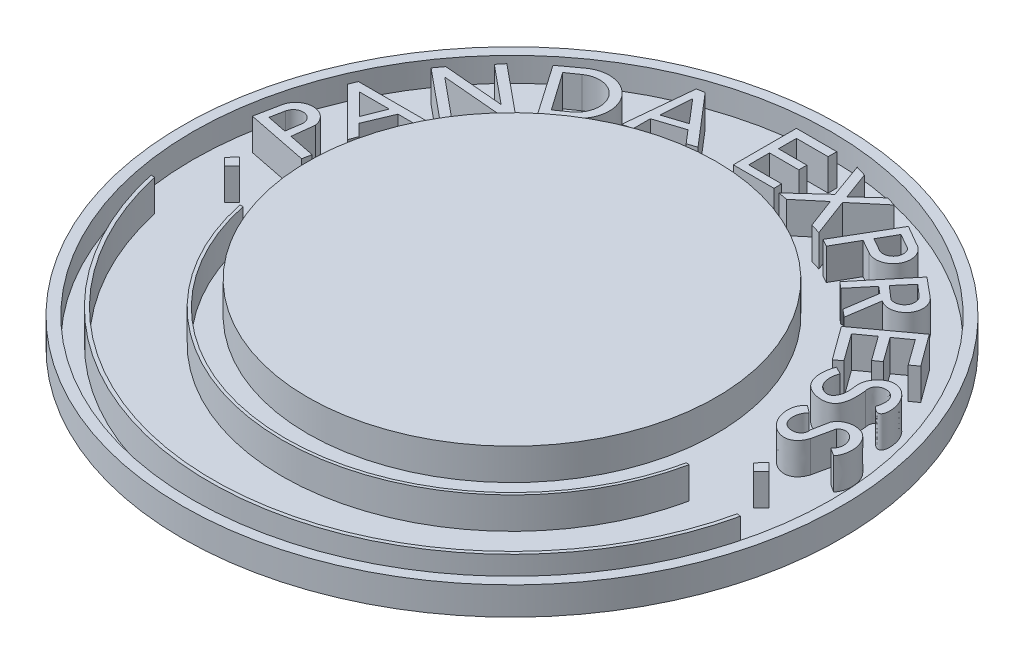
SolidWorks part; units mm, degrees
ref_plane "Front Plane" through (0, 0, 0) normal (0, 0, 1) x (1, 0, 0)
ref_plane "Top Plane" through (0, 0, 0) normal (0, 1, 0) x (1, 0, 0)
ref_plane "Right Plane" through (0, 0, 0) normal (1, 0, 0) x (0, 0, -1)
sketch "Sketch1" plane through (0, 0, 0) normal (0, 1, 0) x (1, 0, 0)
  line L0 (-346.7007, -44.5579) -> (319.966, -44.5579) construction
  line L1 (-334.1811, 33.6432) -> (-331.6592, 46.2527)
  line L2 (-331.6592, 46.2527) -> (-369.4238, 53.8057)
  line L3 (-369.4238, 53.8057) -> (-365.7729, 85.2106)
  line L7 (-414.9002, 86.376) -> (-421.9365, 51.1943)
  line L8 (-421.9365, 51.1943) -> (-334.1811, 33.6432)
  line L9 (-408.6661, 61.5433) -> (-380.3132, 55.8727)
  line L10 (-408.6661, 61.5433) -> (-404.7023, 81.3626)
  line L11 (-380.3132, 55.8727) -> (-376.9852, 77.7838)
  line L12 (-393.6662, 158.4552) -> (-324.9642, 89.7532)
  line L13 (-324.9642, 89.7532) -> (-320.483, 102.2012)
  line L14 (-320.483, 102.2012) -> (-336.9041, 118.6223)
  line L15 (-336.9041, 118.6223) -> (-320.483, 157.6341)
  line L16 (-320.483, 157.6341) -> (-297.8924, 157.6341)
  line L17 (-297.8924, 157.6341) -> (-292.8097, 169.7091)
  line L18 (-292.8097, 169.7091) -> (-388.9291, 169.7091)
  line L19 (-388.9291, 169.7091) -> (-393.6662, 158.4552)
  line L20 (-375.5127, 157.6341) -> (-345.0872, 127.2086)
  line L21 (-345.0872, 127.2086) -> (-332.976, 157.6341)
  line L22 (-332.976, 157.6341) -> (-375.5127, 157.6341)
  line L23 (-354.0443, 238.4507) -> (-285.0479, 181.6814)
  line L24 (-285.0479, 181.6814) -> (-277.2994, 191.0987)
  line L25 (-277.2994, 191.0987) -> (-332.976, 236.9086)
  line L26 (-332.976, 236.9086) -> (-245.7696, 229.4196)
  line L27 (-245.7696, 229.4196) -> (-236.178, 241.077)
  line L28 (-236.178, 241.077) -> (-305.1377, 297.816)
  line L29 (-305.1377, 297.816) -> (-313.2317, 287.9788)
  line L30 (-313.2317, 287.9788) -> (-258.7615, 243.1615)
  line L31 (-258.7615, 243.1615) -> (-345.0872, 250.5748)
  line L32 (-345.0872, 250.5748) -> (-354.0443, 238.4507)
  line L33 (-270.213, 328.7391) -> (-219.7816, 255.8859)
  line L34 (-254.3411, 326.7885) -> (-216.165, 272.3876)
  line L35 (-216.165, 272.3876) -> (-199.6234, 283.9957)
  line L36 (-254.3411, 326.7885) -> (-238.1873, 338.1245)
  line L37 (-270.213, 328.7391) -> (-243.7628, 348.1139)
  line L39 (-219.7816, 255.8859) -> (-194.2095, 274.9236)
  line L40 (-138.6799, 401.8724) -> (-148.2095, 304.4626)
  line L41 (-148.2095, 304.4626) -> (-134.6324, 307.9963)
  line L42 (-134.6324, 307.9963) -> (-134.6324, 332.1748)
  line L43 (-134.6324, 332.1748) -> (-94.0871, 345.3799)
  line L44 (-94.0871, 345.3799) -> (-78.0921, 326.7885)
  line L45 (-78.0921, 326.7885) -> (-65.2948, 330.9565)
  line L46 (-65.2948, 330.9565) -> (-127.9381, 403.7686)
  line L47 (-127.9381, 403.7686) -> (-138.6799, 401.8724)
  line L48 (-129.3219, 387.3889) -> (-100.6881, 353.9057)
  line L49 (-100.6881, 353.9057) -> (-132.2722, 343.6192)
  line L50 (-132.2722, 343.6192) -> (-129.3219, 387.3889)
  line L51 (-18.3874, 424.553) -> (-18.3874, 334.425)
  line L52 (-18.3874, 334.425) -> (39.7046, 334.425)
  line L53 (39.7046, 334.425) -> (39.7046, 345.3799)
  line L54 (39.7046, 345.3799) -> (-7.2816, 345.3799)
  line L55 (-7.2816, 345.3799) -> (-7.2816, 375.0039)
  line L56 (-7.2816, 375.0039) -> (34.5788, 375.0039)
  line L57 (34.5788, 375.0039) -> (34.5788, 386.5369)
  line L58 (34.5788, 386.5369) -> (-6.0002, 386.5369)
  line L59 (-6.0002, 386.5369) -> (-6.0002, 412.1657)
  line L60 (-6.0002, 412.1657) -> (39.2774, 412.1657)
  line L61 (39.2774, 412.1657) -> (39.2774, 424.553)
  line L62 (39.2774, 424.553) -> (-18.3874, 424.553)
  line L63 (73.0154, 419.9703) -> (87.8554, 415.4041)
  line L64 (87.8554, 415.4041) -> (102.3275, 376.0059)
  line L65 (102.3275, 376.0059) -> (132.7562, 403.7686)
  line L66 (132.7562, 403.7686) -> (146.144, 399.6493)
  line L67 (146.144, 399.6493) -> (106.1201, 365.9372)
  line L68 (106.1201, 365.9372) -> (126.5862, 311.6658)
  line L69 (126.5862, 311.6658) -> (112.2084, 316.0897)
  line L70 (112.2084, 316.0897) -> (96.2714, 358.3511)
  line L71 (96.2714, 358.3511) -> (62.3609, 329.7883)
  line L73 (48.795, 332.1748) -> (90.7867, 370.4874)
  line L74 (90.7867, 370.4874) -> (73.0154, 419.9703)
  line L75 (48.795, 332.1748) -> (62.3609, 329.7883)
  line L76 (137.9011, 306.2017) -> (182.8097, 383.3197)
  line L77 (182.8097, 383.3197) -> (209.9717, 367.5023)
  line L78 (148.6297, 300.2705) -> (167.7168, 333.7141)
  line L79 (173.4877, 343.4433) -> (191.4359, 333.1998)
  line L80 (173.4877, 343.4433) -> (187.4893, 367.9763)
  line L81 (187.4893, 367.9763) -> (209.9068, 355.1821)
  line L82 (137.9011, 306.2017) -> (148.6297, 300.2705)
  line L83 (167.7168, 333.7141) -> (187.6976, 322.3105)
  line L84 (258.6263, 333.904) -> (202.1762, 265.9376)
  line L85 (202.1762, 265.9376) -> (211.1619, 258.4745)
  line L86 (211.1619, 258.4745) -> (235.6347, 287.94)
  line L87 (235.6347, 287.94) -> (245.3288, 279.8884)
  line L88 (245.3288, 279.8884) -> (238.4202, 234.1113)
  line L89 (238.4202, 234.1113) -> (249.2216, 225.1401)
  line L90 (249.2216, 225.1401) -> (256.3521, 272.3876)
  line L91 (258.6263, 333.904) -> (286.0361, 311.1385)
  line L92 (242.2645, 296.4948) -> (261.1219, 318.3075)
  line L93 (261.1219, 318.3075) -> (276.3535, 305.1396)
  line L94 (242.2645, 296.4948) -> (260.8123, 280.4599)
  line L95 (258.6263, 211.7516) -> (331.1343, 264.8051)
  line L96 (331.1343, 264.8051) -> (364.4628, 219.2552)
  line L97 (364.4628, 219.2552) -> (354.0732, 211.7516)
  line L98 (354.0732, 211.7516) -> (327.8867, 248.0099)
  line L99 (327.8867, 248.0099) -> (307.0336, 232.9494)
  line L100 (307.0336, 232.9494) -> (332.1396, 198.1873)
  line L101 (332.1396, 198.1873) -> (322.3246, 191.0987)
  line L102 (322.3246, 191.0987) -> (297.2186, 225.8608)
  line L103 (297.2186, 225.8608) -> (274.9902, 209.8069)
  line L104 (274.9902, 209.8069) -> (302.9912, 171.0363)
  line L105 (302.9912, 171.0363) -> (293.3468, 164.0708)
  line L106 (293.3468, 164.0708) -> (258.6263, 211.7516)
  line L107 (305.5325, 157.9393) -> (316.4919, 152.1789)
  line L108 (332.1396, 89.7532) -> (342.9376, 81.4837)
  line L109 (401.4176, 53.8057) -> (413.1035, 46.2527)
  line L110 (369.1928, 85.2106) -> (364.4628, 61.5433)
  line L111 (375.2988, 51.1943) -> (381.9102, 81.4837)
  line L112 (375.2988, -8.5201) -> (386.3772, -19.5985)
  line L113 (386.3772, -19.5985) -> (375.2988, -30.6769)
  line L114 (375.2988, -30.6769) -> (364.4628, -19.841)
  line L115 (364.4628, -19.841) -> (375.2988, -8.5201)
  line L116 (-380.3132, -8.5201) -> (-369.4238, -19.4094)
  line L117 (-369.4238, -19.4094) -> (-380.3132, -30.2988)
  line L118 (-380.3132, -30.2988) -> (-390.9674, -19.6447)
  line L119 (-390.9674, -19.6447) -> (-380.3132, -8.5201)
  line L120 (316.7277, -67.3552) -> (320.8865, -68.2396)
  line L121 (-321.0733, -67.3552) -> (-316.7277, -67.3552)
  line L122 (416.2275, -94.0994) -> (421.2021, -95.2241)
  line L123 (-421.9365, -94.0994) -> (-416.2275, -94.0994)
  circle A0 centre (0, 0) radius 470.6251
  circle A1 centre (0, 0) radius 455.6203
  circle A2 centre (0, 0) radius 291.6875
  arc A3 (-404.7023, 81.3626) -> (-376.9852, 77.7838) centre (-390.9674, 78.6156) cw
  arc A4 (-414.9002, 86.376) -> (-365.7729, 85.2106) centre (-390.4388, 81.4837) cw
  arc A5 (-243.7628, 348.1139) -> (-194.2095, 274.9236) centre (-217.6296, 312.4372) cw
  arc A6 (-238.1873, 338.1245) -> (-199.6234, 283.9957) centre (-219.0983, 310.9227) cw
  arc A7 (191.4359, 333.1998) -> (209.9068, 355.1821) centre (198.669, 345.8734) ccw
  arc A8 (187.6976, 322.3105) -> (209.9717, 367.5023) centre (200.2075, 344.2297) ccw
  arc A9 (276.3535, 305.1396) -> (260.8123, 280.4599) centre (266.7068, 293.9811) cw
  arc A10 (286.0361, 311.1385) -> (256.3521, 272.3876) centre (270.4299, 292.3485) cw
  arc A11 (-316.7277, -67.3552) -> (316.7277, -67.3552) centre (0, 0) ccw
  arc A12 (-321.0733, -67.3552) -> (320.8865, -68.2396) centre (0, 0) ccw
  arc A13 (-421.4548, -94.0994) -> (421.2021, -95.2241) centre (0, 0) ccw
  arc A14 (-416.2275, -94.0994) -> (416.2275, -94.0994) centre (0, 0) ccw
  arc A15 (-352.1943, 240.9548) -> (-353.948, 238.3714) centre (0, 0) ccw
  spline S0 degree 3 poles (316.4919, 152.1789) (312.3414, 142.7699) (313.2525, 122.725) (336.7715, 115.4011) (347.1149, 135.1655) (336.9477, 157.7284) (363.7626, 188.1704) (403.0754, 163.8702) (398.5946, 119.5892) (381.9102, 137.2162) knots 0 0 0 0 0.168105 0.236644 0.306998 0.450025 0.594026 0.79272 1 1 1 1
  spline S1 degree 3 poles (355.4645, 149.3952) (356.6911, 137.6051) (359.0155, 100.6654) (298.5244, 110.1291) (300.6529, 145.0476) (305.5325, 157.9393) knots 0 0 0 0 0.323017 0.634299 1 1 1 1
  spline S2 degree 3 poles (355.4645, 149.3952) (352.0742, 163.1763) (370.4221, 169.9561) (385.9397, 155.4057) (383.9675, 143.3299) (381.9102, 137.2162) knots 0 0 0 0 0.494709 0.645784 1 1 1 1
  spline S3 degree 3 poles (342.9376, 81.4837) (334.2814, 75.3951) (331.7514, 41.8275) (366.9434, 47.0408) (364.4628, 61.5433) knots 0 0 0 0 0.511772 1 1 1 1
  spline S4 degree 3 poles (332.1396, 89.7532) (319.951, 80.1322) (323.3537, 34.869) (367.2901, 26.2786) (375.2988, 51.1943) knots 0 0 0 0 0.459951 1 1 1 1
  spline S5 degree 3 poles (401.4176, 53.8057) (407.8137, 58.6755) (410.1867, 78.2787) (390.5895, 90.3868) (381.9102, 81.4837) knots 0 0 0 0 0.43873 1 1 1 1
  spline S6 degree 3 poles (369.1928, 85.2106) (372.5077, 92.7399) (385.7349, 100.1354) (419.1515, 94.1779) (423.9969, 59.6722) (413.1035, 46.2527) knots 0 0 0 0 0.250574 0.443565 1 1 1 1
  spline S7 degree 3 poles (-78.0921, 180.367) (-37.0889, 192.9309) (-27.979, 201.5598) (36.7421, 189.9503) (41.1355, 188.5225) (53.6592, 176.9745) (58.9179, 200.4658) (75.2354, 202.388) (92.1036, 205.7858) (117.4602, 198.9456) (132.709, 176.253) (136.5726, 156.4078) (128.8024, 146.15) (135.1297, 141.9856) (142.2619, 135.998) (163.4026, 120.484) (178.3854, 104.0711) (187.6976, 89.7532) knots 0 0 0 0 0.408915 0.446676 0.508432 0.521003 0.564665 0.590555 0.63116 0.681705 0.759021 0.80184 0.817987 0.824477 0.847951 0.88494 1 1 1 1
  spline S8 degree 3 poles (187.6976, 89.7532) (201.0991, 73.6352) (214.3714, 50.8009) (229.9271, 14.9067) (233.3462, -14.611) (237.7795, -62.1326) (230.0214, -113.7709) (170.2864, -178.5152) (163.2306, -160.6397) (151.4349, -167.475) (151.342, -178.572) (127.4759, -198.7643) (153.1423, -183.3316) (121.7889, -210.1744) (109.4434, -220.5242) (80.1691, -238.4373) (45.4847, -248.6309) (6.8622, -248.8243) (-22.3974, -226.085) (-16.2768, -198.9703) (2.9072, -185.5434) (20.3945, -162.5088) (14.7668, -129.9117) (-9.0579, -120.2648) (-27.8423, -121.3259) (-43.8396, -132.483) (-45.5203, -149.2124) (-42.9755, -165.426) (-34.1556, -180.1922) (-29.3384, -198.4553) (-37.162, -221.9313) (-65.6583, -228.7044) (-89.9535, -220.6684) (-113.371, -206.9625) (-139.7167, -183.5767) (-165.1081, -153.9512) (-176.1619, -114.8641) (-181.5789, -78.6401) (-163.7548, -28.5407) (-155.3438, -8.9443) (-147.6978, -6.1591) (-153.0561, 8.047) (-156.7314, 20.8219) (-161.7207, 36.2701) (-162.1736, 58.5709) (-159.8698, 79.8853) (-154.7806, 97.6326) (-146.299, 109.7387) (-158.046, 118.4387) (-167.1919, 128.7328) (-175.6027, 147.6055) (-180.1477, 167.2483) (-175.9911, 186.3876) (-164.0023, 201.5832) (-149.7603, 211.8776) (-133.7311, 214.2281) (-119.9812, 215.6561) (-98.8032, 204.0351) (-85.9354, 190.9417) (-78.0921, 180.367) knots 0 0 0 0 0.000844 0.001065 0.001579 0.002026 0.003033 0.00344 0.005796 0.006184 0.006936 0.007485 0.011587 0.01843 0.025739 0.035795 0.049309 0.062457 0.073552 0.079975 0.086854 0.096501 0.107782 0.113287 0.120717 0.125951 0.131087 0.136402 0.142263 0.148033 0.15492 0.164336 0.173351 0.180327 0.191259 0.208518 0.218342 0.230862 0.247485 0.255897 0.314978 0.331296 0.360679 0.398702 0.435771 0.503678 0.532486 0.562212 0.575848 0.616947 0.653699 0.706745 0.744636 0.774819 0.830303 0.851583 0.878974 0.917277 1 1 1 1
  spline S9 degree 3 poles (-149.6371, 111.1185) (-142.6312, 115.6029) (-136.2585, 129.445) (-122.6049, 144.8267) (-104.8697, 163.1114) (-88.877, 173.301) (-78.0921, 180.367) knots 0 0 0 0 0.240964 0.440624 0.613108 1 1 1 1
  spline S10 degree 3 poles (48.795, 181.6814) (44.6124, 175.9442) (39.2378, 166.3266) (38.9908, 151.2109) (44.9831, 138.8316) (55.5945, 126.8512) (68.0852, 116.3399) (80.8951, 107.2319) (95.4859, 100.461) (110.4359, 112.1336) (114.6483, 103.1753) (117.8812, 96.2237) (119.3664, 84.0376) (124.0279, 71.1258) (125.5708, 49.3835) (120.6955, 23.3494) (104.9876, -9.9502) (84.5825, -32.9533) (65.8612, -46.9589) (48.1933, -58.1886) (47.7464, -59.3737) (34.9857, -66.7) (29.6004, -69.9443) (16.8797, -74.6949) (10.2696, -79.6149) (-14.6597, -88.1457) (-21.2371, -92.7249) (-51.6071, -92.3587) (-62.1691, -86.242) (-91.6733, -72.88) (-119.8582, -43.5566) (-119.7484, -40.6363) (-150.3874, 0) knots 0 0 0 0 0.030072 0.044194 0.06163 0.086156 0.110975 0.129708 0.152494 0.175208 0.180464 0.19015 0.208299 0.230698 0.247519 0.298921 0.339633 0.400413 0.426743 0.434868 0.476463 0.485034 0.51201 0.517015 0.530077 0.539586 0.602601 0.619824 0.694595 0.727365 0.914758 1 1 1 1
  spline S11 degree 3 poles (130.6037, 145.4015) (122.9198, 142.2798) (126.8408, 131.6969) (119.0885, 122.9486) (119.1957, 114.1478) (127.7845, 103.4708) (140.6899, 92.0872) (149.9132, 75.152) (160.5704, 59.8653) (165.2604, 40.44) (171.7519, 17.2986) (177.0446, -4.2592) (176.3586, -24.0389) (178.8532, -36.3982) (176.2746, -49.3457) (183.5383, -50.5193) (193.5995, -51.5363) (190.1513, -50.851) (206.302, -48.6749) (209.6555, -48.2309) (220.005, -38.3618) (228.1987, -29.2786) (232.6254, -21.4537) (233.3625, -16.0417) knots 0 0 0 0 0.06437 0.098503 0.12031 0.155601 0.244287 0.311271 0.366755 0.449117 0.52876 0.633684 0.693896 0.741636 0.783828 0.803672 0.809325 0.836913 0.845044 0.887189 0.924208 0.951984 1 1 1 1
  point P220 (0, 0)
  point P228 (0, 0)
  point P232 (196.4188, -50.0164)
  point P236 (187.6976, -50.9164)
  point P240 (0, 0)
  point P252 (0, 0)
extrude "Boss-Extrude1" add sketch "Sketch1" along normal blind 40 contours A0
sketch "Sketch9" plane through (0, 40, 0) normal (0, 1, 0) x (1, 0, 0)
  spline S0 degree 3 poles (2978.0314, -796.2808) (-16.9152, 250.608) (147.9652, 155.5352) (119.0885, 122.9486) (119.1957, 114.1478) (127.7845, 103.4708) (140.6899, 92.0872) (149.9132, 75.152) (160.5704, 59.8653) (165.2604, 40.44) (171.7519, 17.2986) (177.0446, -4.2592) (176.3586, -24.0389) (178.8532, -36.3982) (176.2746, -49.3457) (183.5383, -50.5193) (193.5995, -51.5363) (190.1513, -50.851) (206.302, -48.6749) (209.6555, -48.2309) (220.005, -38.3618) (266.9967, 13.7317) (241.466, 174.4019) (-2760.0738, 7.6653) knots -0.327832 -0.327832 -0.327832 -0.327832 0.06437 0.098503 0.12031 0.155601 0.244287 0.311271 0.366755 0.449117 0.52876 0.633684 0.693896 0.741636 0.783828 0.803672 0.809325 0.836913 0.845044 0.887189 0.924208 0.951984 1.534175 1.534175 1.534175 1.534175 only from (130.6037, 145.4015) to (233.3625, -16.0417) construction
  spline S1 degree 3 poles (-2525.2148, 1939.1592) (-139.6779, -35.9603) (-174.7638, 86.0664) (-122.6049, 144.8267) (-6.391, 264.6416) (318.0431, 140.3304) (-1988.9788, 2473.5674) knots -1.729055 -1.729055 -1.729055 -1.729055 0.240964 0.440624 0.613108 5.214717 5.214717 5.214717 5.214717 only from (-149.6371, 111.1185) to (-78.0921, 180.367) construction
  spline S2 degree 3 poles (-2895.7171, -391.2279) (485.014, 251.5012) (40.6959, 255.5227) (38.9908, 151.2109) (44.9831, 138.8316) (55.5945, 126.8512) (68.0852, 116.3399) (80.8951, 107.2319) (95.4859, 100.461) (110.4359, 112.1336) (114.6483, 103.1753) (117.8812, 96.2237) (119.3664, 84.0376) (124.0279, 71.1258) (125.5708, 49.3835) (120.6955, 23.3494) (104.9876, -9.9502) (84.5825, -32.9533) (65.8612, -46.9589) (48.1933, -58.1886) (47.7464, -59.3737) (34.9857, -66.7) (29.6004, -69.9443) (16.8797, -74.6949) (10.2696, -79.6149) (-14.6597, -88.1457) (-21.2371, -92.7249) (-51.6071, -92.3587) (-62.1691, -86.242) (-91.6733, -72.88) (-142.6253, -19.8698) (-98.8584, -54.3936) (-1990.5908, 2369.0085) knots -0.363673 -0.363673 -0.363673 -0.363673 0.030072 0.044194 0.06163 0.086156 0.110975 0.129708 0.152494 0.175208 0.180464 0.19015 0.208299 0.230698 0.247519 0.298921 0.339633 0.400413 0.426743 0.434868 0.476463 0.485034 0.51201 0.517015 0.530077 0.539586 0.602601 0.619824 0.694595 0.727365 0.914758 1.2467 1.2467 1.2467 1.2467 only from (48.795, 181.6814) to (-150.3874, 0) construction
  spline S3 degree 3 poles (130.6037, 145.4015) (122.9198, 142.2798) (126.8408, 131.6969) (119.0885, 122.9486) (119.1957, 114.1478) (127.7845, 103.4708) (140.6899, 92.0872) (149.9132, 75.152) (160.5704, 59.8653) (165.2604, 40.44) (171.7519, 17.2986) (177.0446, -4.2592) (176.3586, -24.0389) (178.8532, -36.3982) (176.2746, -49.3457) (183.5383, -50.5193) (193.5995, -51.5363) (190.1513, -50.851) (206.302, -48.6749) (209.6555, -48.2309) (220.005, -38.3618) (228.1987, -29.2786) (232.6254, -21.4537) (233.3625, -16.0417) knots 0 0 0 0 0.06437 0.098503 0.12031 0.155601 0.244287 0.311271 0.366755 0.449117 0.52876 0.633684 0.693896 0.741636 0.783828 0.803672 0.809325 0.836913 0.845044 0.887189 0.924208 0.951984 1 1 1 1
  spline S4 degree 3 poles (-149.6371, 111.1185) (-142.6312, 115.6029) (-136.2585, 129.445) (-122.6049, 144.8267) (-104.8697, 163.1114) (-88.877, 173.301) (-78.0921, 180.367) knots 0 0 0 0 0.240964 0.440624 0.613108 1 1 1 1
  spline S5 degree 3 poles (48.795, 181.6814) (44.6124, 175.9442) (39.2378, 166.3266) (38.9908, 151.2109) (44.9831, 138.8316) (55.5945, 126.8512) (68.0852, 116.3399) (80.8951, 107.2319) (95.4859, 100.461) (110.4359, 112.1336) (114.6483, 103.1753) (117.8812, 96.2237) (119.3664, 84.0376) (124.0279, 71.1258) (125.5708, 49.3835) (120.6955, 23.3494) (104.9876, -9.9502) (84.5825, -32.9533) (65.8612, -46.9589) (48.1933, -58.1886) (47.7464, -59.3737) (34.9857, -66.7) (29.6004, -69.9443) (16.8797, -74.6949) (10.2696, -79.6149) (-14.6597, -88.1457) (-21.2371, -92.7249) (-51.6071, -92.3587) (-62.1691, -86.242) (-91.6733, -72.88) (-119.8582, -43.5566) (-119.7484, -40.6363) (-150.3874, 0) knots 0 0 0 0 0.030072 0.044194 0.06163 0.086156 0.110975 0.129708 0.152494 0.175208 0.180464 0.19015 0.208299 0.230698 0.247519 0.298921 0.339633 0.400413 0.426743 0.434868 0.476463 0.485034 0.51201 0.517015 0.530077 0.539586 0.602601 0.619824 0.694595 0.727365 0.914758 1 1 1 1
sketch "Sketch8" plane through (0, 40, 0) normal (0, 1, 0) x (1, 0, 0)
  spline S0 degree 3 poles (-3074.5134, 227.2219) (254.7504, 12.5874) (-179.8145, 228.7955) (36.7421, 189.9503) (41.1355, 188.5225) (53.6592, 176.9745) (58.9179, 200.4658) (75.2354, 202.388) (92.1036, 205.7858) (117.4602, 198.9456) (132.709, 176.253) (136.5726, 156.4078) (128.8024, 146.15) (135.1297, 141.9856) (142.2619, 135.998) (373.3669, -33.5972) (84.1347, -663.1391) (-1196.3584, -2546.2808) knots -1.192778 -1.192778 -1.192778 -1.192778 0.408915 0.446676 0.508432 0.521003 0.564665 0.590555 0.63116 0.681705 0.759021 0.80184 0.817987 0.824477 0.847951 0.88494 2.743243 2.743243 2.743243 2.743243 only from (-78.0921, 180.367) to (187.6976, 89.7532) construction
  spline S1 degree 3 poles (-2426.7162, -1272.6169) (-203.71, 355.1144) (128.2316, 249.5652) (229.9271, 14.9067) (233.3462, -14.611) (237.7795, -62.1326) (230.0214, -113.7709) (170.2864, -178.5152) (163.2306, -160.6397) (151.4349, -167.475) (151.342, -178.572) (127.4759, -198.7643) (153.1423, -183.3316) (121.7889, -210.1744) (109.4434, -220.5242) (80.1691, -238.4373) (45.4847, -248.6309) (6.8622, -248.8243) (-22.3974, -226.085) (-16.2768, -198.9703) (2.9072, -185.5434) (20.3945, -162.5088) (14.7668, -129.9117) (-9.0579, -120.2648) (-27.8423, -121.3259) (-43.8396, -132.483) (-45.5203, -149.2124) (-42.9755, -165.426) (-34.1556, -180.1922) (-29.3384, -198.4553) (-37.162, -221.9313) (-65.6583, -228.7044) (-89.9535, -220.6684) (-113.371, -206.9625) (-139.7167, -183.5767) (-165.1081, -153.9512) (-176.1619, -114.8641) (-181.5789, -78.6401) (-163.7548, -28.5407) (-155.3438, -8.9443) (-147.6978, -6.1591) (-153.0561, 8.047) (-156.7314, 20.8219) (-161.7207, 36.2701) (-162.1736, 58.5709) (-159.8698, 79.8853) (-154.7806, 97.6326) (-146.299, 109.7387) (-158.046, 118.4387) (-167.1919, 128.7328) (-175.6027, 147.6055) (-180.1477, 167.2483) (-175.9911, 186.3876) (-164.0023, 201.5832) (-149.7603, 211.8776) (-133.7311, 214.2281) (-119.9812, 215.6561) (64.2797, 114.5464) (-235.442, -378.8952) (2614.1564, -1018.3453) knots -0.008742 -0.008742 -0.008742 -0.008742 0.000844 0.001065 0.001579 0.002026 0.003033 0.00344 0.005796 0.006184 0.006936 0.007485 0.011587 0.01843 0.025739 0.035795 0.049309 0.062457 0.073552 0.079975 0.086854 0.096501 0.107782 0.113287 0.120717 0.125951 0.131087 0.136402 0.142263 0.148033 0.15492 0.164336 0.173351 0.180327 0.191259 0.208518 0.218342 0.230862 0.247485 0.255897 0.314978 0.331296 0.360679 0.398702 0.435771 0.503678 0.532486 0.562212 0.575848 0.616947 0.653699 0.706745 0.744636 0.774819 0.830303 0.851583 0.878974 0.917277 2.142893 2.142893 2.142893 2.142893 only from (187.6976, 89.7532) to (-78.0921, 180.367) construction
  spline S2 degree 3 poles (-78.0921, 180.367) (-37.0889, 192.9309) (-27.979, 201.5598) (36.7421, 189.9503) (41.1355, 188.5225) (53.6592, 176.9745) (58.9179, 200.4658) (75.2354, 202.388) (92.1036, 205.7858) (117.4602, 198.9456) (132.709, 176.253) (136.5726, 156.4078) (128.8024, 146.15) (135.1297, 141.9856) (142.2619, 135.998) (163.4026, 120.484) (178.3854, 104.0711) (187.6976, 89.7532) knots 0 0 0 0 0.408915 0.446676 0.508432 0.521003 0.564665 0.590555 0.63116 0.681705 0.759021 0.80184 0.817987 0.824477 0.847951 0.88494 1 1 1 1
  spline S3 degree 3 poles (187.6976, 89.7532) (201.0991, 73.6352) (214.3714, 50.8009) (229.9271, 14.9067) (233.3462, -14.611) (237.7795, -62.1326) (230.0214, -113.7709) (170.2864, -178.5152) (163.2306, -160.6397) (151.4349, -167.475) (151.342, -178.572) (127.4759, -198.7643) (153.1423, -183.3316) (121.7889, -210.1744) (109.4434, -220.5242) (80.1691, -238.4373) (45.4847, -248.6309) (6.8622, -248.8243) (-22.3974, -226.085) (-16.2768, -198.9703) (2.9072, -185.5434) (20.3945, -162.5088) (14.7668, -129.9117) (-9.0579, -120.2648) (-27.8423, -121.3259) (-43.8396, -132.483) (-45.5203, -149.2124) (-42.9755, -165.426) (-34.1556, -180.1922) (-29.3384, -198.4553) (-37.162, -221.9313) (-65.6583, -228.7044) (-89.9535, -220.6684) (-113.371, -206.9625) (-139.7167, -183.5767) (-165.1081, -153.9512) (-176.1619, -114.8641) (-181.5789, -78.6401) (-163.7548, -28.5407) (-155.3438, -8.9443) (-147.6978, -6.1591) (-153.0561, 8.047) (-156.7314, 20.8219) (-161.7207, 36.2701) (-162.1736, 58.5709) (-159.8698, 79.8853) (-154.7806, 97.6326) (-146.299, 109.7387) (-158.046, 118.4387) (-167.1919, 128.7328) (-175.6027, 147.6055) (-180.1477, 167.2483) (-175.9911, 186.3876) (-164.0023, 201.5832) (-149.7603, 211.8776) (-133.7311, 214.2281) (-119.9812, 215.6561) (-98.8032, 204.0351) (-85.9354, 190.9417) (-78.0921, 180.367) knots 0 0 0 0 0.000844 0.001065 0.001579 0.002026 0.003033 0.00344 0.005796 0.006184 0.006936 0.007485 0.011587 0.01843 0.025739 0.035795 0.049309 0.062457 0.073552 0.079975 0.086854 0.096501 0.107782 0.113287 0.120717 0.125951 0.131087 0.136402 0.142263 0.148033 0.15492 0.164336 0.173351 0.180327 0.191259 0.208518 0.218342 0.230862 0.247485 0.255897 0.314978 0.331296 0.360679 0.398702 0.435771 0.503678 0.532486 0.562212 0.575848 0.616947 0.653699 0.706745 0.744636 0.774819 0.830303 0.851583 0.878974 0.917277 1 1 1 1
extrude "Cut-Extrude11" cut sketch "Sketch8" against normal blind 25
sketch "Sketch6" plane through (0, 40, 0) normal (0, 1, 0) x (1, 0, 0)
  circle A0 centre (0, 0) radius 291.6875 construction
  circle A1 centre (0, 0) radius 291.6875
extrude "Boss-Extrude3" add sketch "Sketch6" along normal blind 45
sketch "Sketch2" plane through (0, 40, 0) normal (0, 1, 0) x (1, 0, 0)
  circle A0 centre (0, 0) radius 455.6203 construction
  circle A1 centre (0, 0) radius 455.6203
sketch "Sketch3" plane through (0, 40, 0) normal (0, 1, 0) x (1, 0, 0)
  circle A0 centre (0, 0) radius 455.6203 construction
  circle A1 centre (0, 0) radius 455.6203
extrude "Cut-Extrude2" cut sketch "Sketch3" against normal blind 34.6259 contours A1
sketch "Sketch4" plane through (0, 5.3741, 0) normal (0, 1, 0) x (1, 0, 0)
  line L0 (364.4628, -19.841) -> (375.2988, -8.5201) construction
  line L1 (375.2988, -8.5201) -> (386.3772, -19.5985) construction
  line L2 (386.3772, -19.5985) -> (375.2988, -30.6769) construction
  line L3 (375.2988, -30.6769) -> (364.4628, -19.841) construction
  line L4 (-321.0733, -67.3552) -> (-316.7277, -67.3552) construction
  line L5 (316.7277, -67.3552) -> (320.8865, -68.2396) construction
  line L6 (416.2275, -94.0994) -> (421.2021, -95.2241) construction
  line L7 (-421.9365, -94.0994) -> (-416.2275, -94.0994) construction
  line L8 (401.4176, 53.8057) -> (413.1035, 46.2527) construction
  line L9 (332.1396, 89.7532) -> (342.9376, 81.4837) construction
  line L10 (375.2988, 51.1943) -> (381.9102, 81.4837) construction
  line L11 (369.1928, 85.2106) -> (364.4628, 61.5433) construction
  line L12 (305.5325, 157.9393) -> (316.4919, 152.1789) construction
  line L13 (297.2186, 225.8608) -> (274.9902, 209.8069) construction
  line L14 (258.6263, 211.7516) -> (331.1343, 264.8051) construction
  line L15 (327.8867, 248.0099) -> (307.0336, 232.9494) construction
  line L16 (331.1343, 264.8051) -> (364.4628, 219.2552) construction
  line L17 (364.4628, 219.2552) -> (354.0732, 211.7516) construction
  line L18 (354.0732, 211.7516) -> (327.8867, 248.0099) construction
  line L19 (307.0336, 232.9494) -> (332.1396, 198.1873) construction
  line L20 (322.3246, 191.0987) -> (297.2186, 225.8608) construction
  line L21 (332.1396, 198.1873) -> (322.3246, 191.0987) construction
  line L22 (302.9912, 171.0363) -> (293.3468, 164.0708) construction
  line L23 (293.3468, 164.0708) -> (258.6263, 211.7516) construction
  line L24 (274.9902, 209.8069) -> (302.9912, 171.0363) construction
  line L25 (202.1762, 265.9376) -> (211.1619, 258.4745) construction
  line L26 (211.1619, 258.4745) -> (235.6347, 287.94) construction
  line L27 (258.6263, 333.904) -> (202.1762, 265.9376) construction
  line L28 (258.6263, 333.904) -> (286.0361, 311.1385) construction
  line L29 (261.1219, 318.3075) -> (276.3535, 305.1396) construction
  line L30 (242.2645, 296.4948) -> (261.1219, 318.3075) construction
  line L31 (242.2645, 296.4948) -> (260.8123, 280.4599) construction
  line L32 (249.2216, 225.1401) -> (256.3521, 272.3876) construction
  line L33 (238.4202, 234.1113) -> (249.2216, 225.1401) construction
  line L34 (245.3288, 279.8884) -> (238.4202, 234.1113) construction
  line L35 (235.6347, 287.94) -> (245.3288, 279.8884) construction
  line L36 (182.8097, 383.3197) -> (209.9717, 367.5023) construction
  line L37 (187.4893, 367.9763) -> (209.9068, 355.1821) construction
  line L38 (173.4877, 343.4433) -> (187.4893, 367.9763) construction
  line L39 (173.4877, 343.4433) -> (191.4359, 333.1998) construction
  line L40 (167.7168, 333.7141) -> (187.6976, 322.3105) construction
  line L41 (137.9011, 306.2017) -> (182.8097, 383.3197) construction
  line L42 (137.9011, 306.2017) -> (148.6297, 300.2705) construction
  line L43 (148.6297, 300.2705) -> (167.7168, 333.7141) construction
  line L44 (73.0154, 419.9703) -> (87.8554, 415.4041) construction
  line L45 (132.7562, 403.7686) -> (146.144, 399.6493) construction
  line L46 (112.2084, 316.0897) -> (96.2714, 358.3511) construction
  line L47 (126.5862, 311.6658) -> (112.2084, 316.0897) construction
  line L48 (106.1201, 365.9372) -> (126.5862, 311.6658) construction
  line L49 (146.144, 399.6493) -> (106.1201, 365.9372) construction
  line L50 (102.3275, 376.0059) -> (132.7562, 403.7686) construction
  line L51 (87.8554, 415.4041) -> (102.3275, 376.0059) construction
  line L52 (90.7867, 370.4874) -> (73.0154, 419.9703) construction
  line L53 (48.795, 332.1748) -> (90.7867, 370.4874) construction
  line L54 (48.795, 332.1748) -> (62.3609, 329.7883) construction
  line L55 (96.2714, 358.3511) -> (62.3609, 329.7883) construction
  line L56 (-18.3874, 424.553) -> (-18.3874, 334.425) construction
  line L57 (39.7046, 334.425) -> (39.7046, 345.3799) construction
  line L58 (-18.3874, 334.425) -> (39.7046, 334.425) construction
  line L59 (39.7046, 345.3799) -> (-7.2816, 345.3799) construction
  line L60 (-7.2816, 345.3799) -> (-7.2816, 375.0039) construction
  line L61 (34.5788, 375.0039) -> (34.5788, 386.5369) construction
  line L62 (-7.2816, 375.0039) -> (34.5788, 375.0039) construction
  line L63 (-6.0002, 386.5369) -> (-6.0002, 412.1657) construction
  line L64 (34.5788, 386.5369) -> (-6.0002, 386.5369) construction
  line L65 (-6.0002, 412.1657) -> (39.2774, 412.1657) construction
  line L66 (39.2774, 412.1657) -> (39.2774, 424.553) construction
  line L67 (39.2774, 424.553) -> (-18.3874, 424.553) construction
  line L68 (-78.0921, 326.7885) -> (-65.2948, 330.9565) construction
  line L69 (-94.0871, 345.3799) -> (-78.0921, 326.7885) construction
  line L70 (-65.2948, 330.9565) -> (-127.9381, 403.7686) construction
  line L71 (-127.9381, 403.7686) -> (-138.6799, 401.8724) construction
  line L72 (-129.3219, 387.3889) -> (-100.6881, 353.9057) construction
  line L73 (-100.6881, 353.9057) -> (-132.2722, 343.6192) construction
  line L74 (-132.2722, 343.6192) -> (-129.3219, 387.3889) construction
  line L75 (-138.6799, 401.8724) -> (-148.2095, 304.4626) construction
  line L76 (-148.2095, 304.4626) -> (-134.6324, 307.9963) construction
  line L77 (-134.6324, 307.9963) -> (-134.6324, 332.1748) construction
  line L78 (-134.6324, 332.1748) -> (-94.0871, 345.3799) construction
  line L79 (-270.213, 328.7391) -> (-243.7628, 348.1139) construction
  line L80 (-254.3411, 326.7885) -> (-238.1873, 338.1245) construction
  line L81 (-270.213, 328.7391) -> (-219.7816, 255.8859) construction
  line L82 (-254.3411, 326.7885) -> (-216.165, 272.3876) construction
  line L83 (-216.165, 272.3876) -> (-199.6234, 283.9957) construction
  line L84 (-219.7816, 255.8859) -> (-194.2095, 274.9236) construction
  line L85 (-305.1377, 297.816) -> (-313.2317, 287.9788) construction
  line L86 (-236.178, 241.077) -> (-305.1377, 297.816) construction
  line L87 (-245.7696, 229.4196) -> (-236.178, 241.077) construction
  line L88 (-313.2317, 287.9788) -> (-258.7615, 243.1615) construction
  line L89 (-345.0872, 250.5748) -> (-354.0443, 238.4507) construction
  line L90 (-258.7615, 243.1615) -> (-345.0872, 250.5748) construction
  line L91 (-332.976, 236.9086) -> (-245.7696, 229.4196) construction
  line L92 (-277.2994, 191.0987) -> (-332.976, 236.9086) construction
  line L93 (-354.0443, 238.4507) -> (-285.0479, 181.6814) construction
  line L94 (-388.9291, 169.7091) -> (-393.6662, 158.4552) construction
  line L95 (-375.5127, 157.6341) -> (-345.0872, 127.2086) construction
  line L96 (-345.0872, 127.2086) -> (-332.976, 157.6341) construction
  line L97 (-332.976, 157.6341) -> (-375.5127, 157.6341) construction
  line L98 (-292.8097, 169.7091) -> (-388.9291, 169.7091) construction
  line L99 (-297.8924, 157.6341) -> (-292.8097, 169.7091) construction
  line L100 (-320.483, 157.6341) -> (-297.8924, 157.6341) construction
  line L101 (-336.9041, 118.6223) -> (-320.483, 157.6341) construction
  line L102 (-320.483, 102.2012) -> (-336.9041, 118.6223) construction
  line L103 (-324.9642, 89.7532) -> (-320.483, 102.2012) construction
  line L104 (-393.6662, 158.4552) -> (-324.9642, 89.7532) construction
  line L105 (-390.9674, -19.6447) -> (-380.3132, -8.5201) construction
  line L106 (-380.3132, -30.2988) -> (-390.9674, -19.6447) construction
  line L107 (-369.4238, -19.4094) -> (-380.3132, -30.2988) construction
  line L108 (-380.3132, -8.5201) -> (-369.4238, -19.4094) construction
  line L109 (-408.6661, 61.5433) -> (-404.7023, 81.3626) construction
  line L110 (-380.3132, 55.8727) -> (-376.9852, 77.7838) construction
  line L111 (-408.6661, 61.5433) -> (-380.3132, 55.8727) construction
  line L112 (-369.4238, 53.8057) -> (-365.7729, 85.2106) construction
  line L113 (-414.9002, 86.376) -> (-421.9365, 51.1943) construction
  line L114 (-334.1811, 33.6432) -> (-331.6592, 46.2527) construction
  line L115 (-331.6592, 46.2527) -> (-369.4238, 53.8057) construction
  line L116 (-421.9365, 51.1943) -> (-334.1811, 33.6432) construction
  line L117 (364.4628, -19.841) -> (375.2988, -8.5201)
  line L118 (375.2988, -8.5201) -> (386.3772, -19.5985)
  line L119 (386.3772, -19.5985) -> (375.2988, -30.6769)
  line L120 (375.2988, -30.6769) -> (364.4628, -19.841)
  line L121 (-321.0733, -67.3552) -> (-316.7277, -67.3552)
  line L122 (316.7277, -67.3552) -> (320.8865, -68.2396)
  line L123 (416.2275, -94.0994) -> (421.2021, -95.2241)
  line L124 (-421.4548, -94.0994) -> (-416.2275, -94.0994)
  line L125 (401.4176, 53.8057) -> (413.1035, 46.2527)
  line L126 (332.1396, 89.7532) -> (342.9376, 81.4837)
  line L127 (375.2988, 51.1943) -> (381.9102, 81.4837)
  line L128 (369.1928, 85.2106) -> (364.4628, 61.5433)
  line L129 (305.5325, 157.9393) -> (316.4919, 152.1789)
  line L130 (297.2186, 225.8608) -> (274.9902, 209.8069)
  line L131 (258.6263, 211.7516) -> (331.1343, 264.8051)
  line L132 (327.8867, 248.0099) -> (307.0336, 232.9494)
  line L133 (331.1343, 264.8051) -> (364.4628, 219.2552)
  line L134 (364.4628, 219.2552) -> (354.0732, 211.7516)
  line L135 (354.0732, 211.7516) -> (327.8867, 248.0099)
  line L136 (307.0336, 232.9494) -> (332.1396, 198.1873)
  line L137 (322.3246, 191.0987) -> (297.2186, 225.8608)
  line L138 (332.1396, 198.1873) -> (322.3246, 191.0987)
  line L139 (302.9912, 171.0363) -> (293.3468, 164.0708)
  line L140 (293.3468, 164.0708) -> (258.6263, 211.7516)
  line L141 (274.9902, 209.8069) -> (302.9912, 171.0363)
  line L142 (202.1762, 265.9376) -> (211.1619, 258.4745)
  line L143 (211.1619, 258.4745) -> (235.6347, 287.94)
  line L144 (258.6263, 333.904) -> (202.1762, 265.9376)
  line L145 (258.6263, 333.904) -> (286.0361, 311.1385)
  line L146 (261.1219, 318.3075) -> (276.3535, 305.1396)
  line L147 (242.2645, 296.4948) -> (261.1219, 318.3075)
  line L148 (242.2645, 296.4948) -> (260.8123, 280.4599)
  line L149 (249.2216, 225.1401) -> (256.3521, 272.3876)
  line L150 (238.4202, 234.1113) -> (249.2216, 225.1401)
  line L151 (245.3288, 279.8884) -> (238.4202, 234.1113)
  line L152 (235.6347, 287.94) -> (245.3288, 279.8884)
  line L153 (182.8097, 383.3197) -> (209.9717, 367.5023)
  line L154 (187.4893, 367.9763) -> (209.9068, 355.1821)
  line L155 (173.4877, 343.4433) -> (187.4893, 367.9763)
  line L156 (173.4877, 343.4433) -> (191.4359, 333.1998)
  line L157 (167.7168, 333.7141) -> (187.6976, 322.3105)
  line L158 (137.9011, 306.2017) -> (182.8097, 383.3197)
  line L159 (137.9011, 306.2017) -> (148.6297, 300.2705)
  line L160 (148.6297, 300.2705) -> (167.7168, 333.7141)
  line L161 (73.0154, 419.9703) -> (87.8554, 415.4041)
  line L162 (132.7562, 403.7686) -> (146.144, 399.6493)
  line L163 (112.2084, 316.0897) -> (96.2714, 358.3511)
  line L164 (126.5862, 311.6658) -> (112.2084, 316.0897)
  line L165 (106.1201, 365.9372) -> (126.5862, 311.6658)
  line L166 (146.144, 399.6493) -> (106.1201, 365.9372)
  line L167 (102.3275, 376.0059) -> (132.7562, 403.7686)
  line L168 (87.8554, 415.4041) -> (102.3275, 376.0059)
  line L169 (90.7867, 370.4874) -> (73.0154, 419.9703)
  line L170 (48.795, 332.1748) -> (90.7867, 370.4874)
  line L171 (48.795, 332.1748) -> (62.3609, 329.7883)
  line L172 (96.2714, 358.3511) -> (62.3609, 329.7883)
  line L173 (-18.3874, 424.553) -> (-18.3874, 334.425)
  line L174 (39.7046, 334.425) -> (39.7046, 345.3799)
  line L175 (-18.3874, 334.425) -> (39.7046, 334.425)
  line L176 (39.7046, 345.3799) -> (-7.2816, 345.3799)
  line L177 (-7.2816, 345.3799) -> (-7.2816, 375.0039)
  line L178 (34.5788, 375.0039) -> (34.5788, 386.5369)
  line L179 (-7.2816, 375.0039) -> (34.5788, 375.0039)
  line L180 (-6.0002, 386.5369) -> (-6.0002, 412.1657)
  line L181 (34.5788, 386.5369) -> (-6.0002, 386.5369)
  line L182 (-6.0002, 412.1657) -> (39.2774, 412.1657)
  line L183 (39.2774, 412.1657) -> (39.2774, 424.553)
  line L184 (39.2774, 424.553) -> (-18.3874, 424.553)
  line L185 (-78.0921, 326.7885) -> (-65.2948, 330.9565)
  line L186 (-94.0871, 345.3799) -> (-78.0921, 326.7885)
  line L187 (-65.2948, 330.9565) -> (-127.9381, 403.7686)
  line L188 (-127.9381, 403.7686) -> (-138.6799, 401.8724)
  line L189 (-129.3219, 387.3889) -> (-100.6881, 353.9057)
  line L190 (-100.6881, 353.9057) -> (-132.2722, 343.6192)
  line L191 (-132.2722, 343.6192) -> (-129.3219, 387.3889)
  line L192 (-138.6799, 401.8724) -> (-148.2095, 304.4626)
  line L193 (-148.2095, 304.4626) -> (-134.6324, 307.9963)
  line L194 (-134.6324, 307.9963) -> (-134.6324, 332.1748)
  line L195 (-134.6324, 332.1748) -> (-94.0871, 345.3799)
  line L196 (-270.213, 328.7391) -> (-243.7628, 348.1139)
  line L197 (-254.3411, 326.7885) -> (-238.1873, 338.1245)
  line L198 (-270.213, 328.7391) -> (-219.7816, 255.8859)
  line L199 (-254.3411, 326.7885) -> (-216.165, 272.3876)
  line L200 (-216.165, 272.3876) -> (-199.6234, 283.9957)
  line L201 (-219.7816, 255.8859) -> (-194.2095, 274.9236)
  line L202 (-305.1377, 297.816) -> (-313.2317, 287.9788)
  line L203 (-236.178, 241.077) -> (-305.1377, 297.816)
  line L204 (-245.7696, 229.4196) -> (-236.178, 241.077)
  line L205 (-313.2317, 287.9788) -> (-258.7615, 243.1615)
  line L206 (-345.0872, 250.5748) -> (-354.0443, 238.4507)
  line L207 (-258.7615, 243.1615) -> (-345.0872, 250.5748)
  line L208 (-332.976, 236.9086) -> (-245.7696, 229.4196)
  line L209 (-277.2994, 191.0987) -> (-332.976, 236.9086)
  line L210 (-354.0443, 238.4507) -> (-285.0479, 181.6814)
  line L211 (-388.9291, 169.7091) -> (-393.6662, 158.4552)
  line L212 (-375.5127, 157.6341) -> (-345.0872, 127.2086)
  line L213 (-345.0872, 127.2086) -> (-332.976, 157.6341)
  line L214 (-332.976, 157.6341) -> (-375.5127, 157.6341)
  line L215 (-292.8097, 169.7091) -> (-388.9291, 169.7091)
  line L216 (-297.8924, 157.6341) -> (-292.8097, 169.7091)
  line L217 (-320.483, 157.6341) -> (-297.8924, 157.6341)
  line L218 (-336.9041, 118.6223) -> (-320.483, 157.6341)
  line L219 (-320.483, 102.2012) -> (-336.9041, 118.6223)
  line L220 (-324.9642, 89.7532) -> (-320.483, 102.2012)
  line L221 (-393.6662, 158.4552) -> (-324.9642, 89.7532)
  line L222 (-390.9674, -19.6447) -> (-380.3132, -8.5201)
  line L223 (-380.3132, -30.2988) -> (-390.9674, -19.6447)
  line L224 (-369.4238, -19.4094) -> (-380.3132, -30.2988)
  line L225 (-380.3132, -8.5201) -> (-369.4238, -19.4094)
  line L226 (-408.6661, 61.5433) -> (-404.7023, 81.3626)
  line L227 (-380.3132, 55.8727) -> (-376.9852, 77.7838)
  line L228 (-408.6661, 61.5433) -> (-380.3132, 55.8727)
  line L229 (-369.4238, 53.8057) -> (-365.7729, 85.2106)
  line L230 (-414.9002, 86.376) -> (-421.9365, 51.1943)
  line L231 (-334.1811, 33.6432) -> (-331.6592, 46.2527)
  line L232 (-331.6592, 46.2527) -> (-369.4238, 53.8057)
  line L233 (-421.9365, 51.1943) -> (-334.1811, 33.6432)
  line L234 (-285.0479, 181.6814) -> (-277.2994, 191.0987) construction
  line L235 (-285.0479, 181.6814) -> (-277.2994, 191.0987)
  arc A0 (-321.0733, -67.3552) -> (320.8865, -68.2396) centre (0, 0) ccw construction
  arc A1 (-316.7277, -67.3552) -> (316.7277, -67.3552) centre (0, 0) ccw construction
  arc A2 (-421.4548, -94.0994) -> (421.2021, -95.2241) centre (0, 0) ccw construction
  arc A3 (-416.2275, -94.0994) -> (416.2275, -94.0994) centre (0, 0) ccw construction
  arc A4 (260.8123, 280.4599) -> (276.3535, 305.1396) centre (266.7068, 293.9811) ccw construction
  arc A5 (256.3521, 272.3876) -> (286.0361, 311.1385) centre (270.4299, 292.3485) ccw construction
  arc A6 (191.4359, 333.1998) -> (209.9068, 355.1821) centre (198.669, 345.8734) ccw construction
  arc A7 (187.6976, 322.3105) -> (209.9717, 367.5023) centre (200.2075, 344.2297) ccw construction
  arc A8 (-199.6234, 283.9957) -> (-238.1873, 338.1245) centre (-219.0983, 310.9227) ccw construction
  arc A9 (-194.2095, 274.9236) -> (-243.7628, 348.1139) centre (-217.6296, 312.4372) ccw construction
  arc A10 (-376.9852, 77.7838) -> (-404.7023, 81.3626) centre (-390.9674, 78.6156) ccw construction
  arc A11 (-365.7729, 85.2106) -> (-414.9002, 86.376) centre (-390.4388, 81.4837) ccw construction
  arc A12 (-321.0733, -67.3552) -> (320.8865, -68.2396) centre (0, 0) ccw
  arc A13 (-316.7277, -67.3552) -> (316.7277, -67.3552) centre (0, 0) ccw
  arc A14 (-421.4548, -94.0994) -> (421.2021, -95.2241) centre (0, 0) ccw
  arc A15 (-416.2275, -94.0994) -> (416.2275, -94.0994) centre (0, 0) ccw
  arc A16 (260.8123, 280.4599) -> (276.3535, 305.1396) centre (266.7068, 293.9811) ccw
  arc A17 (256.3521, 272.3876) -> (286.0361, 311.1385) centre (270.4299, 292.3485) ccw
  arc A18 (191.4359, 333.1998) -> (209.9068, 355.1821) centre (198.669, 345.8734) ccw
  arc A19 (187.6976, 322.3105) -> (209.9717, 367.5023) centre (200.2075, 344.2297) ccw
  arc A20 (-199.6234, 283.9957) -> (-238.1873, 338.1245) centre (-219.0983, 310.9227) ccw
  arc A21 (-194.2095, 274.9236) -> (-243.7628, 348.1139) centre (-217.6296, 312.4372) ccw
  arc A22 (-376.9852, 77.7838) -> (-404.7023, 81.3626) centre (-390.9674, 78.6156) ccw
  arc A23 (-365.7729, 85.2106) -> (-414.9002, 86.376) centre (-390.4388, 81.4837) ccw
  spline S0 degree 3 poles (1469.7005, -1544.9438) (444.6014, 370.7672) (124.4569, -136.3618) (624.6725, 98.7291) (-794.6673, 1664.6437) knots -1.839586 -1.839586 -1.839586 -1.839586 0.459951 2.659185 2.659185 2.659185 2.659185 only from (332.1396, 89.7532) to (375.2988, 51.1943) construction
  spline S1 degree 3 poles (-658.1383, 1740.3389) (223.8188, -108.8834) (613.1143, 138.9148) (179.8859, 106.1126) (1055.5585, -1796.7135) knots -2.787915 -2.787915 -2.787915 -2.787915 0.43873 3.330752 3.330752 3.330752 3.330752 only from (401.4176, 53.8057) to (381.9102, 81.4837) construction
  spline S2 degree 3 poles (2227.0509, -633.4758) (292.1305, -127.619) (326.3537, 110.7218) (487.653, 81.9656) (299.3834, -353.8636) (-465.1239, 1832.766) knots -1.776994 -1.776994 -1.776994 -1.776994 0.250574 0.443565 3.049922 3.049922 3.049922 3.049922 only from (369.1928, 85.2106) to (413.1035, 46.2527) construction
  spline S3 degree 3 poles (648.4092, -1889.36) (512.3646, 388.9554) (120.2864, -162.1949) (590.6081, 173.2659) (-1511.5053, 742.3359) knots -2.10674 -2.10674 -2.10674 -2.10674 0.511772 2.674685 2.674685 2.674685 2.674685 only from (342.9376, 81.4837) to (364.4628, 61.5433) construction
  spline S4 degree 3 poles (2294.7449, -318.3392) (178.5437, -8.5094) (341.7065, 196.8822) (423.0749, 120.5848) (145.1732, -77.0111) (1526.8094, 1776.4014) knots -1.85053 -1.85053 -1.85053 -1.85053 0.494709 0.645784 3.393119 3.393119 3.393119 3.393119 only from (355.4645, 149.3952) to (381.9102, 137.2162) construction
  spline S5 degree 3 poles (1231.5124, -1648.3575) (142.0552, 518.6154) (444.9706, 87.2179) (190.9707, 126.9555) (608.9912, 525.1354) (-374.9003, -1719.8933) knots -1.420954 -1.420954 -1.420954 -1.420954 0.323017 0.634299 2.778009 2.778009 2.778009 2.778009 only from (355.4645, 149.3952) to (305.5325, 157.9393) construction
  spline S6 degree 3 poles (216.8217, -1840.2356) (544.2918, 491.7001) (245.7461, 143.7469) (336.7715, 115.4011) (347.1149, 135.1655) (336.9477, 157.7284) (363.7626, 188.1704) (442.8237, 139.3008) (323.4695, -51.139) (-172.5469, 2057.2192) knots -0.881173 -0.881173 -0.881173 -0.881173 0.168105 0.236644 0.306998 0.450025 0.594026 0.79272 1.556069 1.556069 1.556069 1.556069 only from (316.4919, 152.1789) to (381.9102, 137.2162) construction
  spline S7 degree 3 poles (332.1396, 89.7532) (319.951, 80.1322) (323.3537, 34.869) (367.2901, 26.2786) (375.2988, 51.1943) knots 0 0 0 0 0.459951 1 1 1 1
  spline S8 degree 3 poles (401.4176, 53.8057) (407.8137, 58.6755) (410.1867, 78.2787) (390.5895, 90.3868) (381.9102, 81.4837) knots 0 0 0 0 0.43873 1 1 1 1
  spline S9 degree 3 poles (369.1928, 85.2106) (372.5077, 92.7399) (385.7349, 100.1354) (419.1515, 94.1779) (423.9969, 59.6722) (413.1035, 46.2527) knots 0 0 0 0 0.250574 0.443565 1 1 1 1
  spline S10 degree 3 poles (342.9376, 81.4837) (334.2814, 75.3951) (331.7514, 41.8275) (366.9434, 47.0408) (364.4628, 61.5433) knots 0 0 0 0 0.511772 1 1 1 1
  spline S11 degree 3 poles (355.4645, 149.3952) (352.0742, 163.1763) (370.4221, 169.9561) (385.9397, 155.4057) (383.9675, 143.3299) (381.9102, 137.2162) knots 0 0 0 0 0.494709 0.645784 1 1 1 1
  spline S12 degree 3 poles (355.4645, 149.3952) (356.6911, 137.6051) (359.0155, 100.6654) (298.5244, 110.1291) (300.6529, 145.0476) (305.5325, 157.9393) knots 0 0 0 0 0.323017 0.634299 1 1 1 1
  spline S13 degree 3 poles (316.4919, 152.1789) (312.3414, 142.7699) (313.2525, 122.725) (336.7715, 115.4011) (347.1149, 135.1655) (336.9477, 157.7284) (363.7626, 188.1704) (403.0754, 163.8702) (398.5946, 119.5892) (381.9102, 137.2162) knots 0 0 0 0 0.168105 0.236644 0.306998 0.450025 0.594026 0.79272 1 1 1 1
extrude "Boss-Extrude2" add sketch "Sketch4" along normal blind 45
sketch "Sketch5" plane through (0, 5.3741, 0) normal (0, 1, 0) x (1, 0, 0)
  circle A0 centre (0, 0) radius 291.6875 construction
  circle A1 centre (0, 0) radius 291.6875
